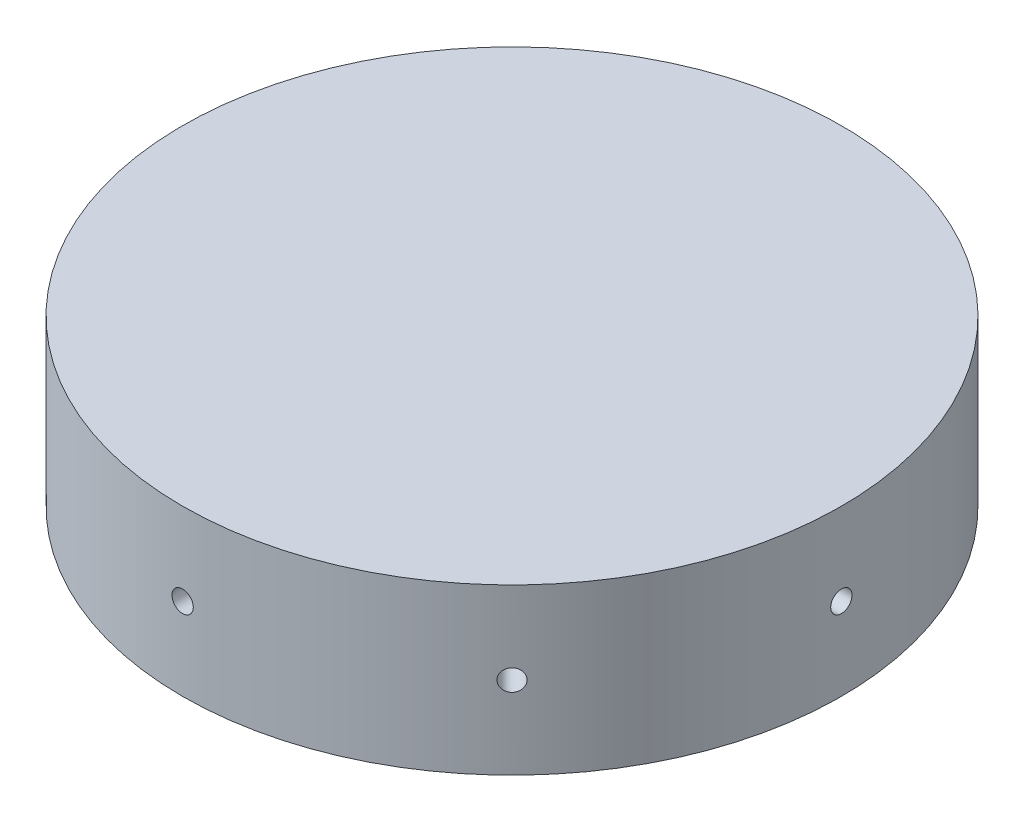
SolidWorks part; units mm, degrees
material "6061 Alloy"
ref_plane "Front Plane" through (0, 0, 0) normal (0, 0, 1) x (1, 0, 0)
ref_plane "Top Plane" through (0, 0, 0) normal (0, 1, 0) x (1, 0, 0)
ref_plane "Right Plane" through (0, 0, 0) normal (1, 0, 0) x (0, 0, -1)
sketch "Sketch1" plane through (0, 0, 0) normal (0, 1, 0) x (1, 0, 0)
  circle A0 centre (0, 0) radius 50.8
  dimension "D1" = 101.6
extrude "Bulkhead Extrusion" add sketch "Sketch1" along normal blind 25.4
ref_plane "Plane1" through (0, 0, 50.8) normal (0, 0, 1) x (1, 0, 0)
sketch "Sketch2" plane through (0, 0, 50.8) normal (0, 0, 1) x (1, 0, 0)
  line L0 (0, 25.4) -> (0, 0) construction
  line L1 (50.8, 25.4) -> (-50.8, 25.4) construction
  circle A0 centre (0, 12.7) radius 1.6383
  dimension "D1" = 3.2766
extrude "Screw Hole" cut sketch "Sketch2" against normal blind 12.7
pattern_circular "CirPattern1" count 8 over 360 about axis through (0, 0, 0) along (0, 1, 0) of "Screw Hole"
